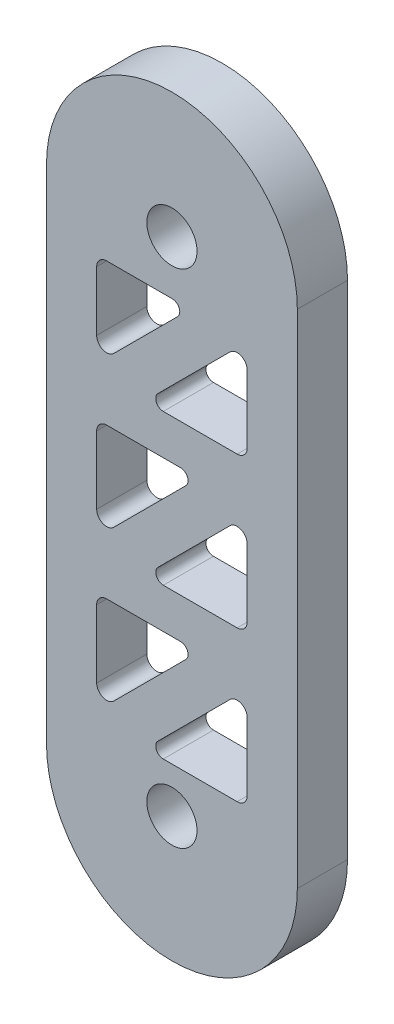
SolidWorks part; units mm, degrees
ref_plane "Front Plane" through (0, 0, 0) normal (0, 0, 1) x (1, 0, 0)
ref_plane "Top Plane" through (0, 0, 0) normal (0, 1, 0) x (1, 0, 0)
ref_plane "Right Plane" through (0, 0, 0) normal (1, 0, 0) x (0, 0, -1)
sketch "Sketch1" plane through (0, 0, 0) normal (0, 0, 1) x (1, 0, 0)
  line L0 (15, 0) -> (15, 100)
  line L2 (0, 0) -> (0, 100)
  line L4 (50, 0) -> (50, 100)
  line L5 (35, 0) -> (35, 100)
  arc A0 (50, 100) -> (0, 100) centre (25, 100) ccw
  arc A1 (0, 0) -> (50, 0) centre (25, 0) ccw
  circle A2 centre (25, 0) radius 5
  circle A3 centre (25, 100) radius 5
  arc A4 (35, 100) -> (15, 100) centre (25, 100) ccw
  arc A5 (15, 0) -> (35, 0) centre (25, 0) ccw
  point P16 (0, 0)
  point P18 (0, 0)
  dimension "D3" = 10
  dimension "D4" = 10
  dimension "D1" = 100
  dimension "D2" = 50
  dimension "D5" = 15
extrude "Boss-Extrude1" add sketch "Sketch1" along normal blind 10 contours L2 A1 L4 A0 A5 L0 A4 L5 | L0 A5 L5 A4 A2 A3
sketch "Sketch2" plane through (0, 0, 10) normal (0, 0, 1) x (1, 0, 0)
  line L0 (10, 100) -> (10, 0)
  line L1 (40, 0) -> (40, 100)
  line L2 (0, 100) -> (0, 0)
  line L3 (50, 0) -> (50, 100)
  line L4 (0, 100) -> (0, 0)
  line L5 (50, 0) -> (50, 100)
  line L6 (25, 99) -> (25, 100) construction
  line L7 (25.065, 89.3431) -> (10, 89.3431)
  line L16 (23.2782, 9) -> (40, 9)
  line L17 (40, 29.3431) -> (22.2175, 11.5607)
  line L18 (23.2782, 39) -> (40, 39)
  line L19 (27.8284, 47.1716) -> (22.2175, 41.5607)
  line L20 (27.8284, 47.1716) -> (40, 59.3431)
  line L21 (40, 69) -> (23.2782, 69)
  line L22 (22.2175, 71.5607) -> (40, 89.3431)
  line L25 (27.7825, 28.4393) -> (10, 10.6569)
  line L26 (10, 31) -> (26.7218, 31)
  line L27 (22.1716, 52.8284) -> (10, 40.6569)
  line L28 (22.1716, 52.8284) -> (27.7825, 58.4393)
  line L29 (26.7218, 61) -> (10, 61)
  line L30 (10, 70.6569) -> (26.1256, 86.7825)
  line L47 (25, 89.3431) -> (25, 91) construction
  arc A0 (10, 0) -> (40, 0) centre (25, 0) ccw
  arc A1 (40, 100) -> (10, 100) centre (25, 100) ccw
  arc A2 (0, 0) -> (50, 0) centre (25, 0) ccw
  arc A3 (50, 100) -> (0, 100) centre (25, 100) ccw
  arc A4 (0, 0) -> (50, 0) centre (25, 0) ccw
  arc A5 (50, 100) -> (0, 100) centre (25, 100) ccw
  arc A6 (26.1256, 86.7825) -> (25.065, 89.3431) centre (25.065, 87.8431) ccw
  arc A7 (22.2175, 71.5607) -> (23.2782, 69) centre (23.2782, 70.5) ccw
  arc A8 (26.7218, 61) -> (27.7825, 58.4393) centre (26.7218, 59.5) cw
  arc A9 (22.2175, 41.5607) -> (23.2782, 39) centre (23.2782, 40.5) ccw
  arc A10 (26.7218, 31) -> (27.7825, 28.4393) centre (26.7218, 29.5) cw
  arc A11 (22.2175, 11.5607) -> (23.2782, 9) centre (23.2782, 10.5) ccw
  dimension "D3" = 1.5
  dimension "D1" = 0
  dimension "D2" = 10
extrude "Cut-Extrude2" cut sketch "Sketch2" against normal blind 10 contours L30 A6 L7 L0 | L22 A7 L21 L1 | A8 L29 L0 L27 L28 | L19 A9 L18 L1 L20 | A10 L26 L0 L25 | L17 A11 L16 L1
fillet "Fillet1" radius 2 12 edges at (40, 89.3431, 5) (40, 69, 5) (10, 89.3431, 5) (10, 70.6569, 5) (10, 40.6569, 5) (10, 61, 5) (40, 59.3431, 5) (10, 31, 5) (10, 10.6569, 5) (40, 29.3431, 5) (40, 9, 5) (40, 39, 5)
